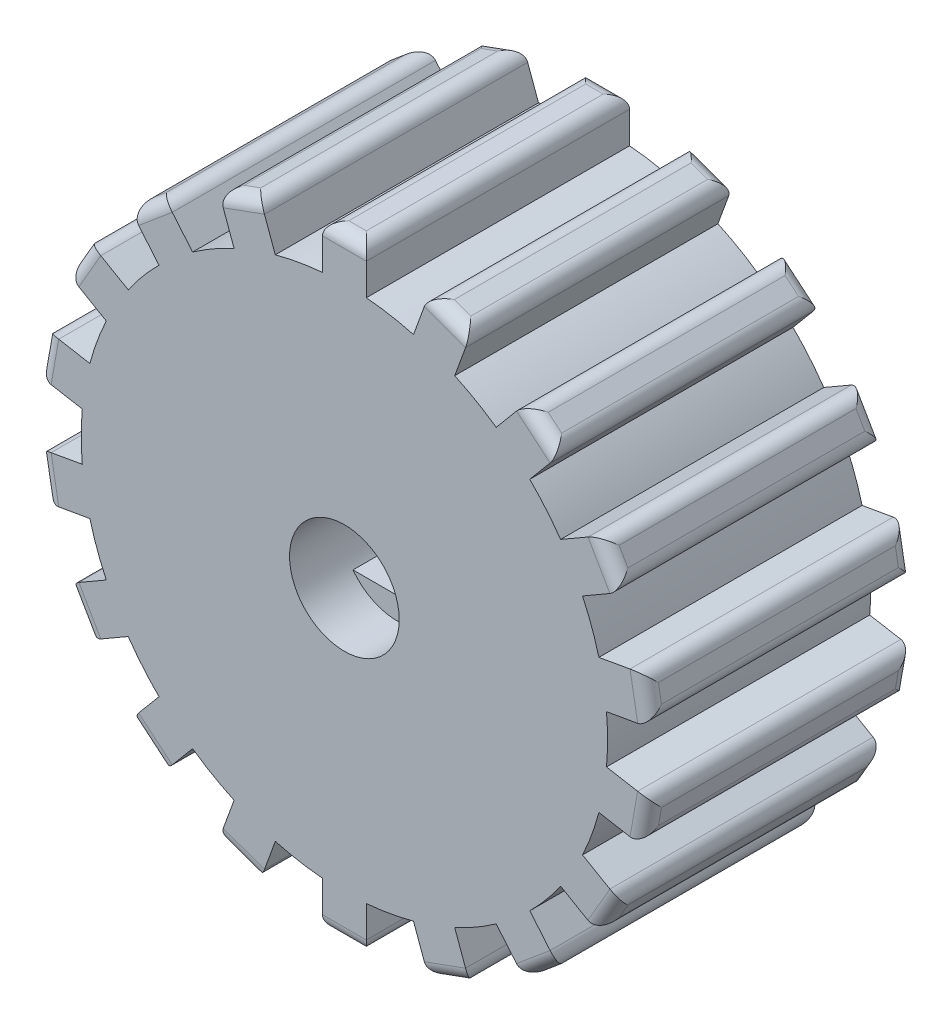
SolidWorks part; units mm, degrees
ref_plane "Front Plane" through (0, 0, 0) normal (0, 0, 1) x (1, 0, 0)
ref_plane "Top Plane" through (0, 0, 0) normal (0, 1, 0) x (1, 0, 0)
ref_plane "Right Plane" through (0, 0, 0) normal (1, 0, 0) x (0, 0, -1)
sketch "Sketch2" plane through (0, 0, 0) normal (0, 0, 1) x (1, 0, 0)
  circle A0 centre (0, 0) radius 60
extrude "Boss-Extrude1" add sketch "Sketch2" along normal blind 60
sketch "Sketch3" plane through (0, 0, 60) normal (0, 0, 1) x (1, 0, 0)
  line L0 (0, 60) -> (0, 70) construction
  line L1 (5, 70) -> (-5, 70)
  line L2 (-5, 70) -> (-5, 59.5215)
  line L3 (-5, 59.5215) -> (5, 59.5215)
  line L4 (5, 59.5215) -> (5, 70)
  circle A0 centre (0, 0) radius 60 construction
  point P9 (0, 70)
extrude "Boss-Extrude2" add sketch "Sketch3" against normal blind 60
fillet "Fillet2" radius 3 4 edges at (-5, 70, 30) (0, 70, 60) (0, 70, 0) (5, 70, 30)
pattern_circular "CirPattern1" count 18 over 360 about axis through (0, 0, 0) along (0, 0, 1) of "Fillet2", "Boss-Extrude2"
sketch "Sketch4" plane through (0, 0, 60) normal (0, 0, 1) x (1, 0, 0)
  circle A0 centre (0, 0) radius 10
extrude "Cut-Extrude1" cut sketch "Sketch4" against normal blind 60
sketch "Sketch5" plane through (0, 0, 60) normal (0, 0, 1) x (1, 0, 0)
  circle A0 centre (0, 0) radius 22.4818
extrude "Boss-Extrude3" add sketch "Sketch5" against normal blind 60
sketch "Sketch6" plane through (0, 0, 60) normal (0, 0, 1) x (1, 0, 0)
  circle A0 centre (0, 0) radius 12.5
extrude "Cut-Extrude2" cut sketch "Sketch6" against normal blind 12
sketch "Sketch7" plane through (0, 0, 48) normal (0, 0, 1) x (1, 0, 0)
  line L1 (10.0373, -7.45) -> (-10.0373, -7.45)
  line L3 (10.0373, 7.45) -> (-10.0373, 7.45)
  arc A0 (-10.0373, 7.45) -> (-10.0373, -7.45) centre (0, 0) ccw
  arc A1 (10.0373, -7.45) -> (10.0373, 7.45) centre (0, 0) ccw
  point P0 (0, 0)
extrude "Cut-Extrude3" cut sketch "Sketch7" against normal blind 30.5
